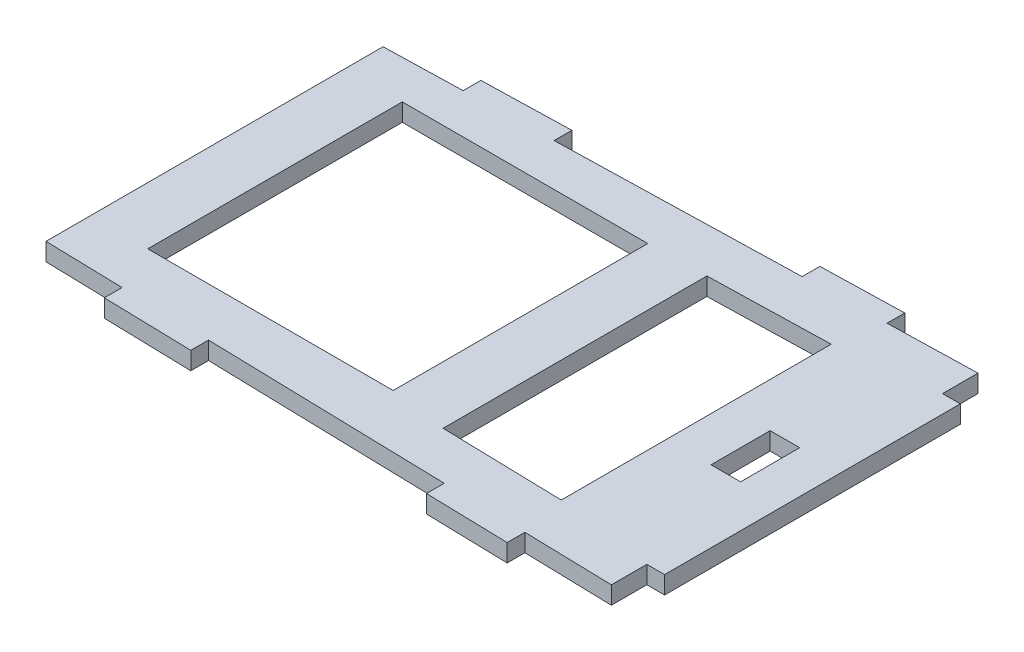
SolidWorks part; units mm, degrees
ref_plane "Front Plane" through (0, 0, 0) normal (0, 0, 1) x (1, 0, 0)
ref_plane "Top Plane" through (0, 0, 0) normal (0, 1, 0) x (1, 0, 0)
ref_plane "Right Plane" through (0, 0, 0) normal (1, 0, 0) x (0, 0, -1)
sketch "Sketch1" plane through (0, 0, 0) normal (0, 1, 0) x (1, 0, 0)
  line L0 (0, -28.5) -> (0, 28.5)
  line L1 (98.1, 31) -> (83.1, 30.6177)
  line L2 (13.2, 28.8364) -> (13.2, 31.8374)
  line L3 (101.1, -34.0774) -> (101.1, 34.0774)
  line L4 (13.2, 31.8374) -> (28.2, 32.2196)
  line L5 (13.2, 31.8374) -> (28.2, 32.2196)
  line L6 (28.2, 32.2196) -> (28.2, 29.2187)
  line L7 (28.2, 29.2187) -> (69.1, 30.261)
  line L8 (69.1, 30.261) -> (69.1, 33.2619)
  line L9 (69.1, 33.2619) -> (83.1, 33.6187)
  line L10 (13.2, 28.8364) -> (0, 28.5)
  line L11 (69.1, 33.2619) -> (83.1, 33.6187)
  line L12 (83.1, 33.6187) -> (83.1, 30.6177)
  line L13 (83.1, 30.6177) -> (98.1, 31)
  line L14 (98.1, 31) -> (98.1, 34.001) construction
  line L15 (98.1, 34.001) -> (101.1, 34.0774) construction
  line L16 (98.1, 31) -> (98.1, 25)
  line L17 (98.1, 25) -> (101.1, 25)
  line L18 (0, 0) -> (101.1, 0) construction
  line L19 (98.1, -34.001) -> (101.1, -34.0774) construction
  line L20 (98.1, -31) -> (98.1, -34.001) construction
  line L21 (98.1, -25) -> (101.1, -25)
  line L22 (98.1, -31) -> (98.1, -25)
  line L23 (83.1, -30.6177) -> (98.1, -31)
  line L24 (83.1, -33.6187) -> (83.1, -30.6177)
  line L25 (69.1, -33.2619) -> (83.1, -33.6187)
  line L26 (13.2, -28.8364) -> (0, -28.5)
  line L27 (69.1, -33.2619) -> (83.1, -33.6187)
  line L28 (69.1, -30.261) -> (69.1, -33.2619)
  line L29 (28.2, -29.2187) -> (69.1, -30.261)
  line L30 (28.2, -32.2196) -> (28.2, -29.2187)
  line L31 (13.2, -31.8374) -> (28.2, -32.2196)
  line L32 (13.2, -31.8374) -> (28.2, -32.2196)
  line L33 (13.2, -28.8364) -> (13.2, -31.8374)
  line L34 (98.1, -31) -> (83.1, -30.6177)
  line L35 (69.1, 30.261) -> (28.2, 29.2187)
  line L36 (69.1, -30.261) -> (28.2, -29.2187)
  line L37 (101.1, 25) -> (101.1, -25)
  point P4 (0, 0)
  point P10 (101.1, 0)
  point P35 (101.1, 0)
  dimension "D1" = 57
  dimension "D2" = 3
  dimension "D3" = 13.2
  dimension "D4" = 50
  dimension "D5" = 101.1
  dimension "D6" = 15
  dimension "D7" = 40.9
  dimension "D8" = 14
  dimension "D9" = 15
  dimension "D10" = 6
  dimension "D11" = 3
extrude "Boss-Extrude1" add sketch "Sketch1" against normal blind 3 contours L34 L23 L22 L21 L3 L17 L16 L1 L6 L4 L2 L10 L0 L26 L33 L31 L30 L29
sketch "Sketch2" plane through (0, -3, 0) normal (0, -1, 0) x (1, 0, 0)
  line L0 (81.45, 22.8232) -> (9.7, 20.9947) construction
  line L1 (0, 28.5) -> (0, -28.5) construction
  line L2 (13.2, 28.8364) -> (0, 28.5) construction
  line L3 (9.7, -20.9947) -> (9.7, 20.9947)
  line L4 (9.7, 20.9947) -> (51.2, 22.0523)
  line L5 (0, 0) -> (101.1, 0) construction
  line L6 (0, 0) -> (101.1, 0) construction
  line L7 (81.45, -22.8232) -> (9.7, -20.9947) construction
  line L9 (51.2, 22.0523) -> (51.2, -22.0523)
  line L10 (60.95, 22.3007) -> (60.95, -22.3007)
  line L11 (81.45, 22.8232) -> (81.45, -22.8232)
  line L12 (60.95, 0) -> (93.95, 0) construction
  line L13 (93.95, 0) -> (93.95, 5)
  line L14 (93.95, 5) -> (88.95, 5)
  line L15 (88.95, 5) -> (88.95, -5)
  line L16 (88.95, -5) -> (93.95, -5)
  line L17 (93.95, -5) -> (93.95, 0)
  line L18 (9.7, 20.9947) -> (9.7, -20.9947)
  line L19 (60.95, -22.3007) -> (81.45, -22.8232)
  line L20 (60.95, 22.3007) -> (81.45, 22.8232)
  line L21 (9.7, 20.9947) -> (51.2, 20.9947)
  line L22 (9.7, 20.9947) -> (9.7, -22.0523)
  line L23 (9.7, -22.0523) -> (51.2, -22.0523)
  line L24 (51.2, 20.9947) -> (51.2, -22.0523)
  dimension "D1" = 7.75
  dimension "D2" = 41.5
  dimension "D3" = 9.7
  dimension "D4" = 9.75
  dimension "D5" = 20.5
  dimension "D6" = 33
extrude "Cut-Extrude1" cut sketch "Sketch2" against normal blind 3 contours L16 L17 L13 L14 L15 | L20 L11 L19 L10 | L22 L21 L24 L23
